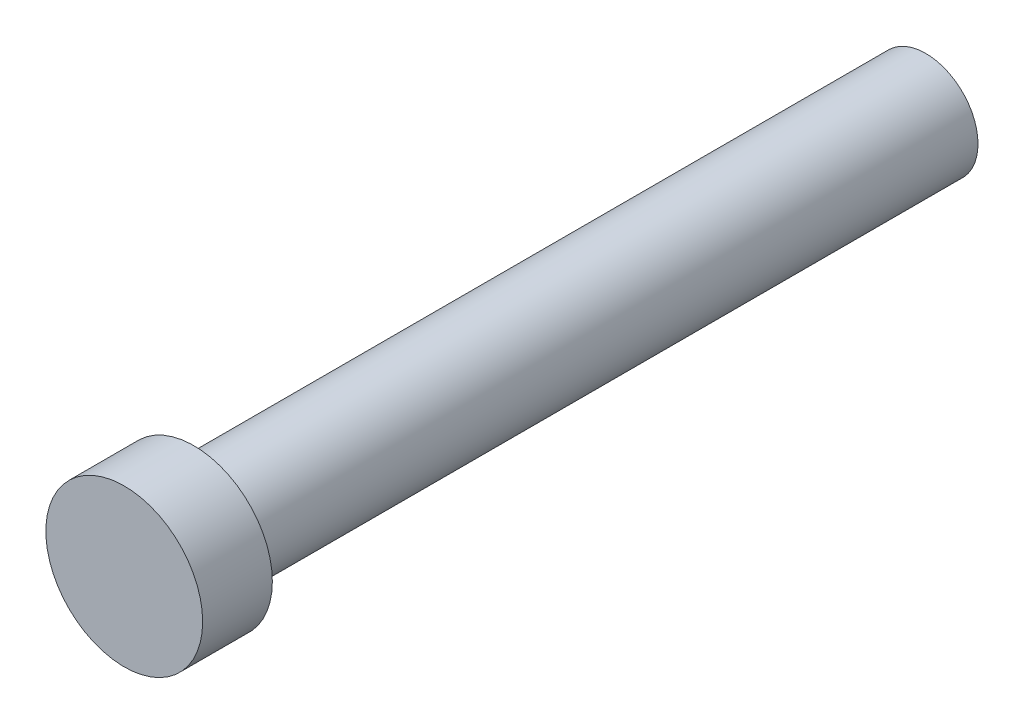
SolidWorks part; units mm, degrees
ref_plane "Front Plane" through (0, 0, 0) normal (0, 0, 1) x (1, 0, 0)
ref_plane "Top Plane" through (0, 0, 0) normal (0, 1, 0) x (1, 0, 0)
ref_plane "Right Plane" through (0, 0, 0) normal (1, 0, 0) x (0, 0, -1)
sketch "Sketch1" plane through (0, 0, 0) normal (0, 0, 1) x (1, 0, 0)
  circle A0 centre (0, 0) radius 22.5
extrude "Boss-Extrude1" add sketch "Sketch1" along normal blind 20
sketch "Sketch2" plane through (0, 0, 0) normal (1, 0, 0) x (0, 0, -1)
  line L0 (-38.4034, 0) -> (230.5162, 0) construction
  line L1 (0, 15) -> (0, 0)
  line L2 (0, -22.5) -> (0, 22.5) construction
  line L3 (0, 15) -> (210, 15)
  line L4 (210, 15) -> (210, 0)
  line L5 (0, 0) -> (210, 0)
revolve "Revolve2" add sketch "Sketch2" angle 360 about L0
